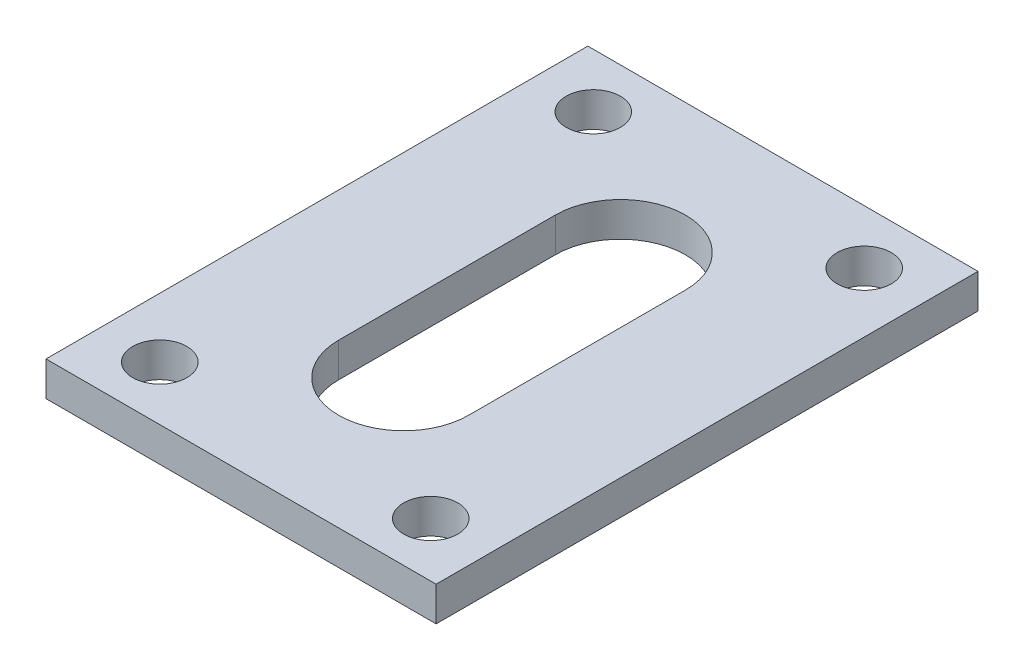
SolidWorks part; units mm, degrees
ref_plane "Front" through (0, 0, 0) normal (0, 0, 1) x (1, 0, 0)
ref_plane "Top" through (0, 0, 0) normal (0, 1, 0) x (1, 0, 0)
ref_plane "Right" through (0, 0, 0) normal (1, 0, 0) x (0, 0, -1)
sketch "Sketch1" plane through (0, 0, 0) normal (0, 1, 0) x (1, 0, 0)
  line L1 (-18, 25) -> (18, 25)
  line L2 (-18, 25) -> (-18, -25)
  line L3 (-18, -25) -> (18, -25)
  line L4 (18, 25) -> (18, -25)
  line L5 (-18, 25) -> (18, -25) construction
  line L6 (-18, -25) -> (18, 25) construction
  point P0 (0, 0)
  dimension "D1" = 36
  dimension "D2" = 50
extrude "Boss-Extrude1" add sketch "Sketch1" along normal blind 3.175
sketch "Sketch3" plane through (0, 3.175, 0) normal (0, 1, 0) x (1, 0, 0)
  line L1 (-12.5, 20) -> (12.5, 20) construction
  line L2 (-12.5, 20) -> (-12.5, -20) construction
  line L3 (-12.5, -20) -> (12.5, -20) construction
  line L4 (12.5, 20) -> (12.5, -20) construction
  line L5 (-12.5, 20) -> (12.5, -20) construction
  line L6 (-12.5, -20) -> (12.5, 20) construction
  circle A0 centre (-12.5, 20) radius 2.5
  circle A1 centre (12.5, 20) radius 2.5
  circle A2 centre (12.5, -20) radius 2.5
  circle A3 centre (-12.5, -20) radius 2.5
  point P0 (0, 0)
  dimension "D3" = 5
  dimension "D1" = 40
  dimension "D2" = 25
extrude "Cut-Extrude1" cut sketch "Sketch3" against normal up to next
sketch "Sketch4" plane through (0, 3.175, 0) normal (0, 1, 0) x (1, 0, 0)
  line L0 (0, -10) -> (0, 10) construction
  line L1 (-6, -10) -> (-6, 10)
  line L2 (6, -10) -> (6, 10)
  line L3 (0, 25) -> (0, -25) construction
  line L4 (18, 25) -> (-18, 25) construction
  line L5 (-18, -25) -> (18, -25) construction
  arc A0 (-6, -10) -> (6, -10) centre (0, -10) ccw
  arc A1 (6, 10) -> (-6, 10) centre (0, 10) ccw
  point P3 (0, 0)
  dimension "D1" = 20
  dimension "D2" = 12
extrude "Cut-Extrude2" cut sketch "Sketch4" against normal up to next
